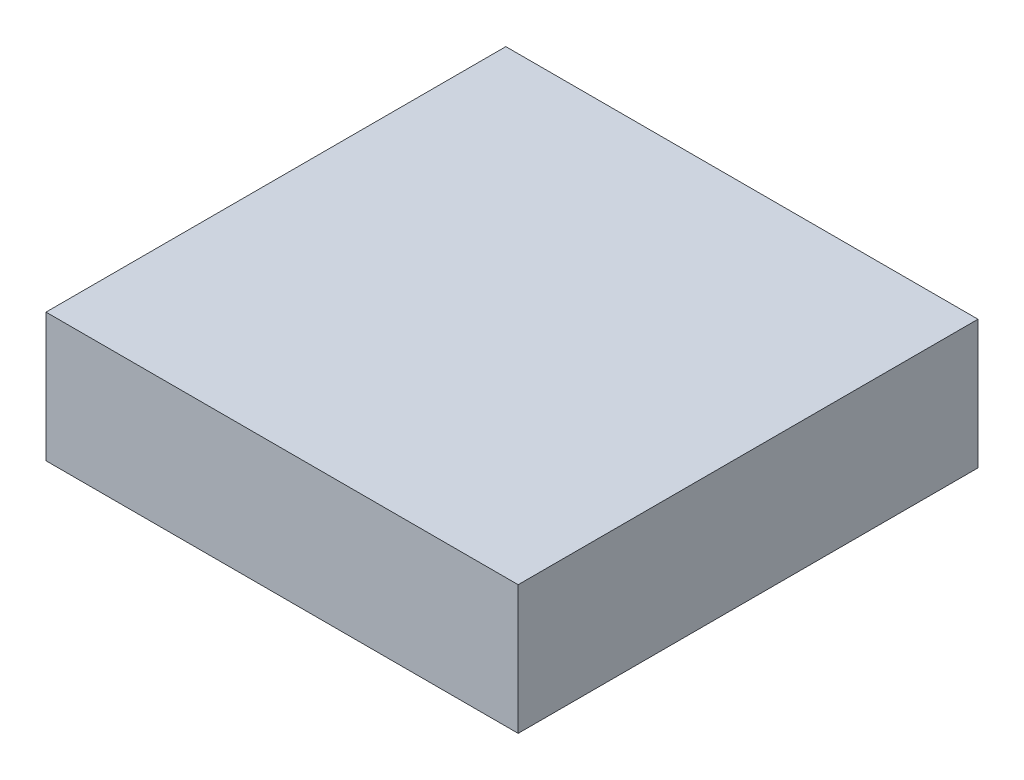
SolidWorks part; units mm, degrees
ref_plane "Front Plane" through (0, 0, 0) normal (0, 0, 1) x (1, 0, 0)
ref_plane "Top Plane" through (0, 0, 0) normal (0, 1, 0) x (1, 0, 0)
ref_plane "Right Plane" through (0, 0, 0) normal (1, 0, 0) x (0, 0, -1)
sketch "Sketch1" plane through (0, 0, 0) normal (0, 0, 1) x (1, 0, 0)
  line L1 (0, 0) -> (33, 0)
  line L2 (0, 0) -> (0, 9)
  line L3 (0, 9) -> (33, 9)
  line L4 (33, 0) -> (33, 9)
  dimension "D1" = 9
  dimension "D2" = 33
extrude "Boss-Extrude1" add sketch "Sketch1" along normal blind 32.1391
